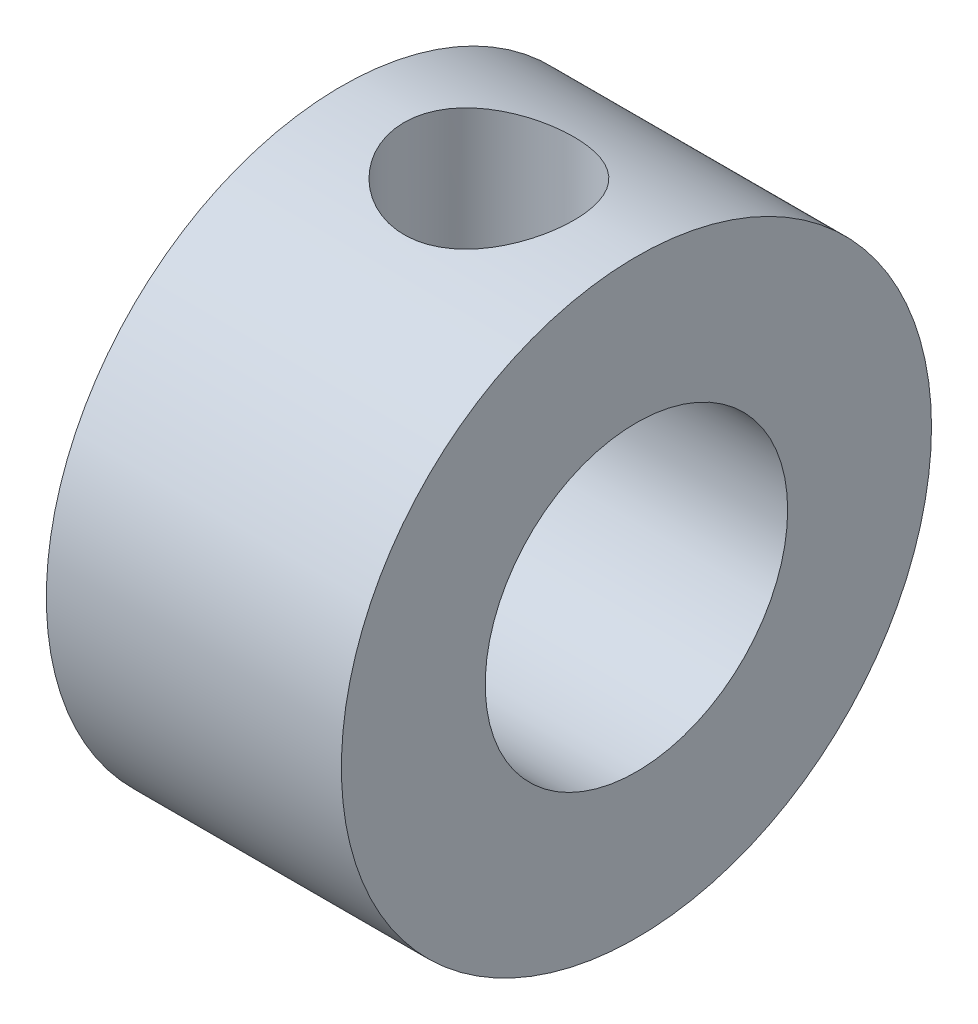
SolidWorks part; units mm, degrees
ref_plane "前视基准面" through (0, 0, 0) normal (0, 0, 1) x (1, 0, 0)
ref_plane "上视基准面" through (0, 0, 0) normal (0, 1, 0) x (1, 0, 0)
ref_plane "右视基准面" through (0, 0, 0) normal (1, 0, 0) x (0, 0, -1)
sketch "草图1" plane through (0, 0, 0) normal (1, 0, 0) x (0, 0, -1)
  circle A0 centre (0, 0) radius 4
  circle A1 centre (0, 0) radius 2.05
  dimension "D1" = 8
  dimension "D2" = 4.1
extrude "凸台-拉伸1" add sketch "草图1" along normal blind 4
sketch "草图2" plane through (0, 0, 0) normal (0, 1, 0) x (1, 0, 0)
  line L0 (0, 0) -> (2, 0) construction
  line L1 (0, 4) -> (0, -4) construction
  circle A0 centre (2, 0) radius 1.15
  dimension "D2" = 2.3
  dimension "D1" = 2
extrude "切除-拉伸1" cut sketch "草图2" along normal blind 5
cosmetic thread "装饰螺纹线1" parameters "D2"=3
